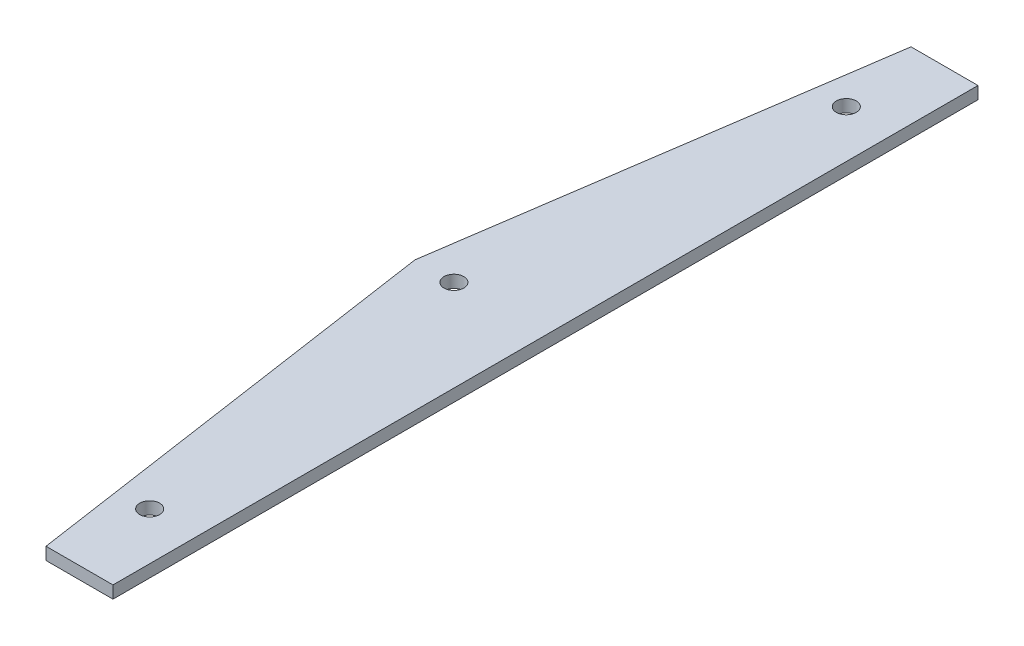
SolidWorks part; units mm, degrees
ref_plane "Front Plane" through (0, 0, 0) normal (0, 0, 1) x (1, 0, 0)
ref_plane "Top Plane" through (0, 0, 0) normal (0, 1, 0) x (1, 0, 0)
ref_plane "Right Plane" through (0, 0, 0) normal (1, 0, 0) x (0, 0, -1)
sketch "Sketch1" plane through (0, 7.6595, 0) normal (0, 1, 0) x (1, 0, 0)
  line L0 (-167.8237, -6.7743) -> (114.1763, -6.7743) construction
  line L1 (-141.5163, 104.251) -> (-124.3237, 104.251)
  line L3 (-141.5163, -117.7997) -> (-124.3237, -117.7997)
  line L4 (-124.3237, 104.251) -> (-124.3237, -117.7997)
  line L5 (-136.5163, 82.6365) -> (-136.5163, 125.8656) construction
  line L7 (-144.3237, 125.8656) -> (90.6763, 125.8656) construction
  line L8 (-141.5163, 104.251) -> (-157.8295, -6.7743)
  line L9 (-157.8295, -6.7743) -> (-141.5163, -117.7997)
  circle A0 centre (-147.8295, -6.7743) radius 2.5527 construction
  circle A1 centre (-136.5163, -96.1851) radius 2.5527 construction
  circle A2 centre (-136.5163, 82.6365) radius 2.5527 construction
  circle A3 centre (-136.5163, -96.1851) radius 2.5527
  circle A4 centre (-147.8295, -6.7743) radius 2.5527
  circle A5 centre (-136.5163, 82.6365) radius 2.5527
  point P8 (-136.5163, 104.251)
  point P10 (-124.3237, -6.7743)
  dimension "D1" = 10
extrude "Boss-Extrude1" add sketch "Sketch1" against normal blind 3.175
